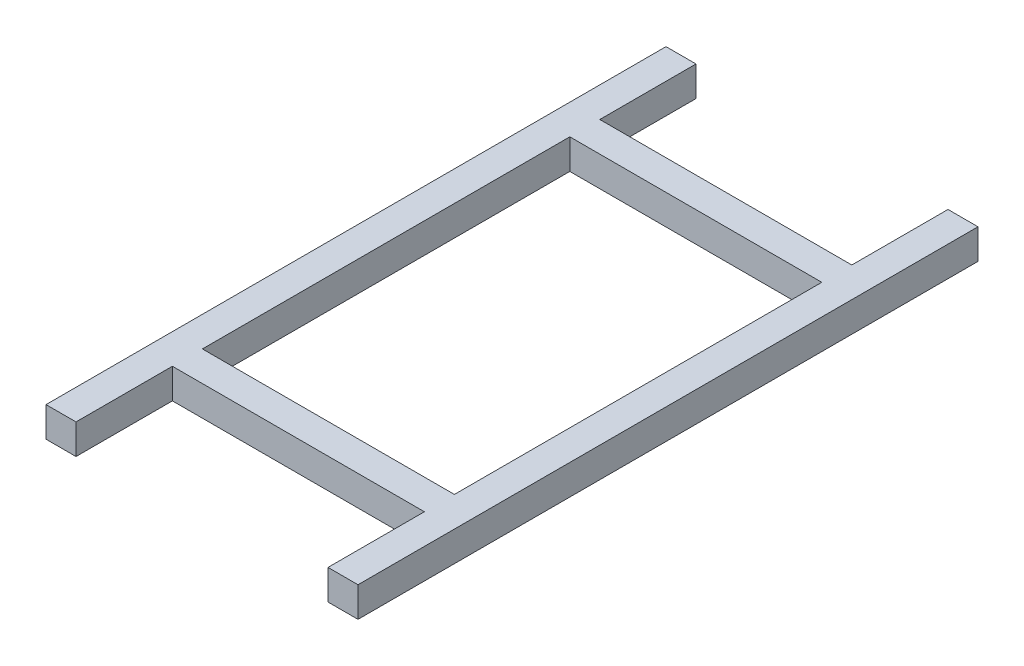
SolidWorks part; units mm, degrees
ref_plane "Front Plane" through (0, 0, 0) normal (0, 0, 1) x (1, 0, 0)
ref_plane "Top Plane" through (0, 0, 0) normal (0, 1, 0) x (1, 0, 0)
ref_plane "Right Plane" through (0, 0, 0) normal (1, 0, 0) x (0, 0, -1)
sketch "Sketch1" plane through (0, 0, 0) normal (0, 0, 1) x (1, 0, 0)
  line L0 (1340.1159, 31.4603) -> (1490.1159, 31.4603)
  line L1 (-69.8841, 31.4603) -> (80.1159, 31.4603)
  line L2 (-69.8841, 31.4603) -> (-69.8841, -118.5397)
  line L3 (-69.8841, -118.5397) -> (80.1159, -118.5397)
  line L4 (80.1159, 31.4603) -> (80.1159, -118.5397)
  line L5 (1340.1159, 31.4603) -> (1340.1159, -118.5397)
  line L6 (1340.1159, -118.5397) -> (1490.1159, -118.5397)
  line L7 (1490.1159, 31.4603) -> (1490.1159, -118.5397)
  dimension "D1" = 1260
extrude "Boss-Extrude1" add sketch "Sketch1" along normal blind 3100
sketch "Sketch2" plane through (80.1159, 0, 0) normal (1, 0, 0) x (0, 0, -1)
  line L0 (-3100, 31.4603) -> (0, 31.4603) construction
  line L1 (-2618, -118.5397) -> (-2468, -118.5397)
  line L2 (-2618, -118.5397) -> (-2618, 31.4603)
  line L3 (-2618, 31.4603) -> (-2468, 31.4603)
  line L4 (-2468, -118.5397) -> (-2468, 31.4603)
  line L5 (-2618, -118.5397) -> (-2325, -118.5397) construction
  line L6 (-3100, -118.5397) -> (0, -118.5397) construction
  line L7 (-2325, -118.5397) -> (-775, -118.5397) construction
  line L8 (-630.9825, -118.5397) -> (-480.9825, -118.5397)
  line L9 (-630.9825, -118.5397) -> (-630.9825, 31.4603)
  line L10 (-630.9825, 31.4603) -> (-480.9825, 31.4603)
  line L11 (-480.9825, -118.5397) -> (-480.9825, 31.4603)
  dimension "D1" = 150
  dimension "D2" = 150
  dimension "D3" = 150
extrude "Boss-Extrude2" add sketch "Sketch2" along normal up to next
